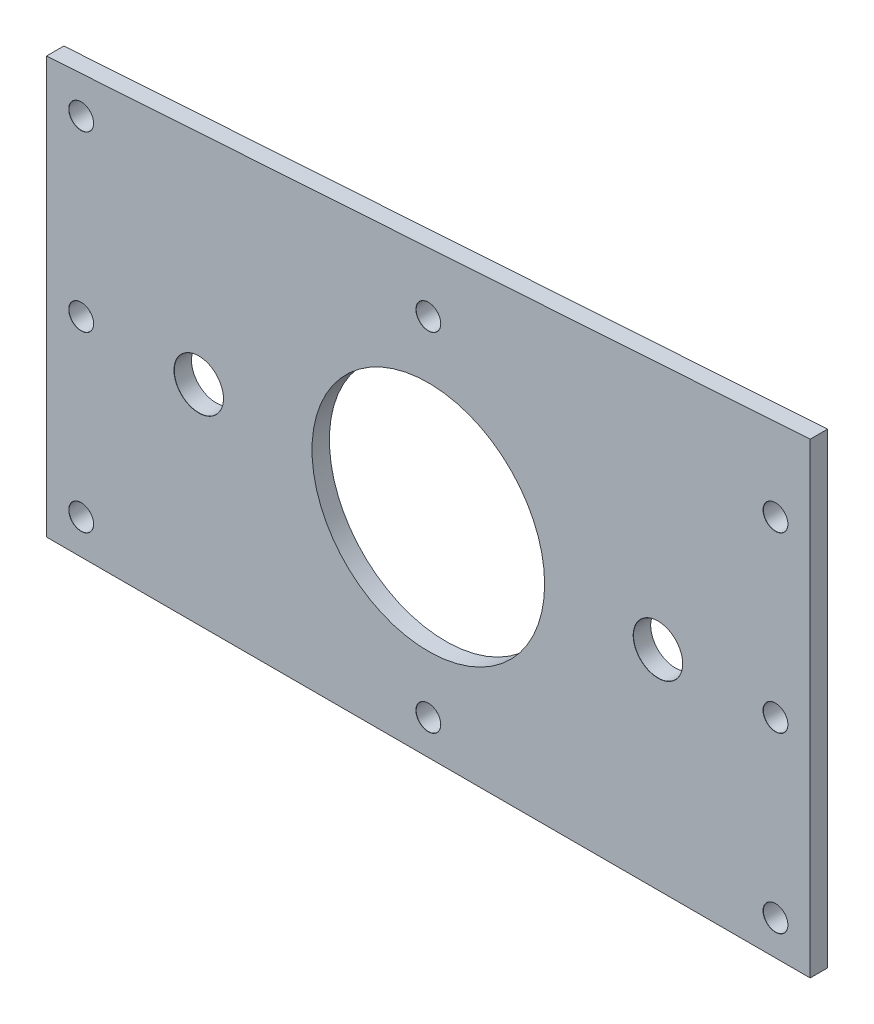
SolidWorks part; units mm, degrees
material "Custom Plastic"
ref_plane "X-Y Datum" through (0, 0, 0) normal (0, 0, 1) x (1, 0, 0)
ref_plane "X-Z Datum" through (0, 0, 0) normal (0, 1, 0) x (1, 0, 0)
ref_plane "Y-Z Datum" through (0, 0, 0) normal (1, 0, 0) x (0, 0, -1)
sketch "Sketch1" plane through (0, 0, 0) normal (0, 0, 1) x (1, 0, 0)
  line L0 (-69.85, 38.1) -> (69.85, 47.2564)
  line L1 (-69.85, 38.1) -> (69.85, 38.1) construction
  line L2 (-69.85, 38.1) -> (-69.85, -38.1)
  line L3 (-69.85, -38.1) -> (69.85, -38.1)
  line L4 (69.85, 38.1) -> (69.85, -38.1)
  line L5 (-69.85, 38.1) -> (69.85, -38.1) construction
  line L6 (-69.85, -38.1) -> (69.85, 38.1) construction
  line L7 (69.85, 38.1) -> (69.85, 47.2564)
  point P0 (0, 0)
  dimension "D1" = 139.7
  dimension "D2" = 76.2
  dimension "D3" = 3.75
  dimension "D4" = 9.1564
extrude "Boss-Extrude1" add sketch "Sketch1" along normal blind 3.175
hole_wizard "M4 Clearance Hole1" positions "Sketch7" profile "Sketch8" hole size "M4" standard "ANSI Metric" end condition through all
sketch "Sketch7" plane through (0, 0, 3.175) normal (0, 0, 1) x (1, 0, 0)
  line L0 (-75.8701, 0) -> (49924.1299, 0) construction
  line L1 (0, 56.7764) -> (0, -49943.2236) construction
  line L2 (-69.85, -38.1) -> (69.85, -38.1) construction
  line L3 (-69.85, 38.1) -> (-69.85, -38.1) construction
  circle A0 centre (-63.5, -31.75) radius 6.35
  circle A1 centre (-63.5, 31.75) radius 6.35
  circle A2 centre (63.5, -31.75) radius 6.35
  circle A3 centre (63.5, 31.75) radius 6.35
  circle A4 centre (-63.5, 0) radius 6.35
  circle A5 centre (0, -31.75) radius 6.35
  circle A6 centre (63.5, 0) radius 6.35
  circle A7 centre (0, 31.75) radius 6.35
  point P0 (-63.5, -31.75)
  point P2 (0, -31.75)
  point P4 (63.5, -31.75)
  point P6 (63.5, 31.75)
  point P8 (63.5, 0)
  point P10 (0, 31.75)
  point P12 (-63.5, 31.75)
  point P14 (-63.5, 0)
  dimension "D1" = 12.7
sketch "Sketch8" plane through (-63.5, -31.75, 3.175) normal (1, 0, 0) x (0, -1, 0)
  line L0 (0, 0) -> (0, 3.175)
  line L1 (0, 3.175) -> (2.25, 3.175)
  line L2 (2.25, 3.175) -> (2.25, 0.025)
  line L3 (2.25, 0.025) -> (2.275, 0)
  line L5 (2.275, 0) -> (0, 0)
  line L6 (-2.25, 0.025) -> (-2.275, 0) construction
  line L11 (0, -6.35) -> (0, 107.95) construction
  dimension "Thru Hole Dia." = 4.5
  dimension "Thru Hole Depth" = 3.175
  dimension "Near C'Sink Dia." = 4.55
  dimension "Near C'Sink Angle" = 90
sketch "Sketch9" plane through (0, 0, 3.175) normal (0, 0, 1) x (1, 0, 0)
  line L0 (-42, 0) -> (42, 0) construction
  line L1 (0, -38.1) -> (0, 42.6782) construction
  line L2 (-69.85, -38.1) -> (69.85, -38.1) construction
  line L3 (69.85, 47.2564) -> (-69.85, 38.1) construction
  circle A0 centre (0, 0) radius 21.275
  circle A1 centre (42, 0) radius 4 construction
  circle A2 centre (-42, 0) radius 4 construction
  dimension "D1" = 42.55
  dimension "D3" = 8
  dimension "D2" = 42
hole_wizard "M8 Clearance Hole1" positions "Sketch10" profile "Sketch11" hole size "M8" standard "ANSI Metric" end condition through all
sketch "Sketch10" plane through (0, 0, 3.175) normal (0, 0, 1) x (1, 0, 0)
  point P0 (-42, 0)
  point P3 (42, 0)
sketch "Sketch11" plane through (-42, 0, 3.175) normal (1, 0, 0) x (0, -1, 0)
  line L0 (0, 0) -> (0, 3.175)
  line L1 (0, 3.175) -> (4.5, 3.175)
  line L2 (4.5, 3.175) -> (4.5, 0.025)
  line L3 (4.5, 0.025) -> (4.525, 0)
  line L5 (4.525, 0) -> (0, 0)
  line L6 (-4.5, 0.025) -> (-4.525, 0) construction
  line L11 (0, -6.35) -> (0, 107.95) construction
  dimension "Thru Hole Dia." = 9
  dimension "Thru Hole Depth" = 3.175
  dimension "Near C'Sink Dia." = 9.05
  dimension "Near C'Sink Angle" = 90
extrude "Center Hole" cut sketch "Sketch9" against normal through all
